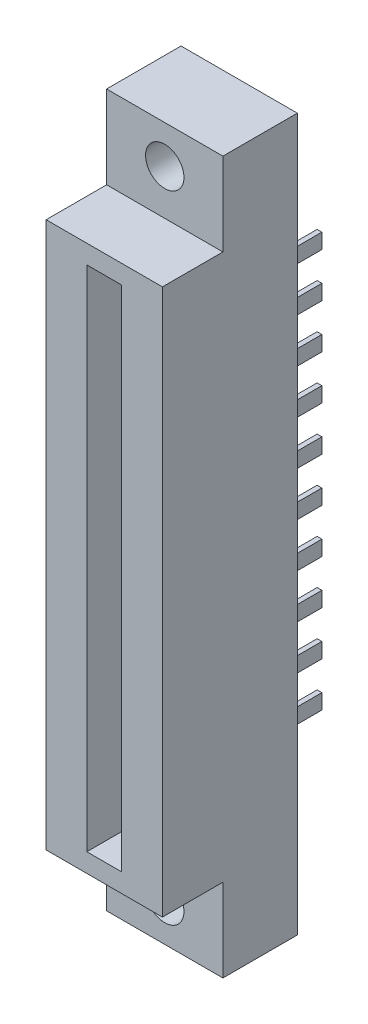
SolidWorks part; units mm, degrees
ref_plane "前视基准面" through (0, 0, 0) normal (0, 0, 1) x (1, 0, 0)
ref_plane "上视基准面" through (0, 0, 0) normal (0, 1, 0) x (1, 0, 0)
ref_plane "右视基准面" through (0, 0, 0) normal (1, 0, 0) x (0, 0, -1)
sketch "草图1" plane through (0, 0, 0) normal (0, 0, 1) x (1, 0, 0)
  line L0 (-109.3839, 0) -> (104.0581, 0) construction
  line L1 (0, 55.921) -> (0, -57.9694) construction
  line L3 (-5, 30.6) -> (5, 30.6)
  line L4 (-5, 30.6) -> (-5, -30.6)
  line L5 (-5, -30.6) -> (5, -30.6)
  line L6 (5, 30.6) -> (5, -30.6)
  dimension "D1" = 61.2
  dimension "D2" = 10
extrude "拉伸1" add sketch "草图1" along normal blind 6.4
sketch "草图2" plane through (0, 0, 6.4) normal (0, 0, 1) x (1, 0, 0)
  line L0 (-8.8552, 0) -> (12.3972, 0) construction
  line L1 (0, 34.0186) -> (0, -32.3951) construction
  line L3 (-5, 30.6) -> (-5, -30.6) construction
  line L4 (-5, 23.465) -> (5, 23.465)
  line L5 (-5, 23.465) -> (-5, -23.465)
  line L6 (-5, -23.465) -> (5, -23.465)
  line L7 (5, 23.465) -> (5, -23.465)
  line L8 (5, -30.6) -> (5, 30.6) construction
  dimension "D1" = 46.93
extrude "拉伸2" add sketch "草图2" along normal blind 5.2
sketch "草图3" plane through (0, 0, 6.4) normal (0, 0, 1) x (1, 0, 0)
  line L0 (-13.2827, 0) -> (15.9393, 0) construction
  line L1 (0, 37.0608) -> (0, -37.8999) construction
  circle A0 centre (0, 27.335) radius 1.65
  circle A1 centre (0, -27.335) radius 1.65
  dimension "D1" = 3.3
  dimension "D2" = 54.67
extrude "切除-拉伸1" cut sketch "草图3" against normal blind 15.3
sketch "草图4" plane through (0, 0, 0) normal (0, 0, -1) x (-1, 0, 0)
  line L0 (-14.0207, 1.905) -> (16.6772, 1.905) construction
  line L1 (0, 36.8227) -> (0, -37.1179) construction
  line L2 (-1.905, 0.2963) -> (-1.905, 4.0459) construction
  line L3 (-2.11, 2.555) -> (-1.7, 2.555)
  line L4 (-2.11, 2.555) -> (-2.11, 1.255)
  line L5 (-2.11, 1.255) -> (-1.7, 1.255)
  line L6 (-1.7, 2.555) -> (-1.7, 1.255)
  line L7 (1.905, 0.2963) -> (1.905, 4.0459) construction
  line L8 (1.7, 2.555) -> (1.7, 1.255)
  line L9 (2.11, 1.255) -> (1.7, 1.255)
  line L10 (2.11, 2.555) -> (2.11, 1.255)
  line L11 (2.11, 2.555) -> (1.7, 2.555)
  line L12 (-2.11, 6.365) -> (-1.7, 6.365)
  line L13 (-2.11, 6.365) -> (-2.11, 5.065)
  line L14 (-2.11, 5.065) -> (-1.7, 5.065)
  line L15 (-1.7, 6.365) -> (-1.7, 5.065)
  line L16 (1.7, 6.365) -> (1.7, 5.065)
  line L17 (2.11, 5.065) -> (1.7, 5.065)
  line L18 (2.11, 6.365) -> (2.11, 5.065)
  line L19 (2.11, 6.365) -> (1.7, 6.365)
  line L20 (-1.905, 4.1063) -> (-1.905, 7.8559) construction
  line L21 (1.905, 4.1063) -> (1.905, 7.8559) construction
  line L22 (-2.11, 10.175) -> (-1.7, 10.175)
  line L23 (-2.11, 10.175) -> (-2.11, 8.875)
  line L24 (-2.11, 8.875) -> (-1.7, 8.875)
  line L25 (-1.7, 10.175) -> (-1.7, 8.875)
  line L26 (1.7, 10.175) -> (1.7, 8.875)
  line L27 (2.11, 8.875) -> (1.7, 8.875)
  line L28 (2.11, 10.175) -> (2.11, 8.875)
  line L29 (2.11, 10.175) -> (1.7, 10.175)
  line L30 (-1.905, 7.9163) -> (-1.905, 11.6659) construction
  line L31 (1.905, 7.9163) -> (1.905, 11.6659) construction
  line L32 (-2.11, 13.985) -> (-1.7, 13.985)
  line L33 (-2.11, 13.985) -> (-2.11, 12.685)
  line L34 (-2.11, 12.685) -> (-1.7, 12.685)
  line L35 (-1.7, 13.985) -> (-1.7, 12.685)
  line L36 (1.7, 13.985) -> (1.7, 12.685)
  line L37 (2.11, 12.685) -> (1.7, 12.685)
  line L38 (2.11, 13.985) -> (2.11, 12.685)
  line L39 (2.11, 13.985) -> (1.7, 13.985)
  line L40 (-1.905, 11.7263) -> (-1.905, 15.4759) construction
  line L41 (1.905, 11.7263) -> (1.905, 15.4759) construction
  line L42 (-2.11, 17.795) -> (-1.7, 17.795)
  line L43 (-2.11, 17.795) -> (-2.11, 16.495)
  line L44 (-2.11, 16.495) -> (-1.7, 16.495)
  line L45 (-1.7, 17.795) -> (-1.7, 16.495)
  line L46 (1.7, 17.795) -> (1.7, 16.495)
  line L47 (2.11, 16.495) -> (1.7, 16.495)
  line L48 (2.11, 17.795) -> (2.11, 16.495)
  line L49 (2.11, 17.795) -> (1.7, 17.795)
  line L50 (-1.905, 15.5363) -> (-1.905, 19.2859) construction
  line L51 (1.905, 15.5363) -> (1.905, 19.2859) construction
  line L52 (-2.11, -1.255) -> (-1.7, -1.255)
  line L53 (-2.11, -1.255) -> (-2.11, -2.555)
  line L54 (-2.11, -2.555) -> (-1.7, -2.555)
  line L55 (-1.7, -1.255) -> (-1.7, -2.555)
  line L56 (1.7, -1.255) -> (1.7, -2.555)
  line L57 (2.11, -2.555) -> (1.7, -2.555)
  line L58 (2.11, -1.255) -> (2.11, -2.555)
  line L59 (2.11, -1.255) -> (1.7, -1.255)
  line L60 (-2.11, -5.065) -> (-1.7, -5.065)
  line L61 (-2.11, -5.065) -> (-2.11, -6.365)
  line L62 (-2.11, -6.365) -> (-1.7, -6.365)
  line L63 (-1.7, -5.065) -> (-1.7, -6.365)
  line L64 (1.7, -5.065) -> (1.7, -6.365)
  line L65 (2.11, -6.365) -> (1.7, -6.365)
  line L66 (2.11, -5.065) -> (2.11, -6.365)
  line L67 (2.11, -5.065) -> (1.7, -5.065)
  line L68 (-2.11, -8.875) -> (-1.7, -8.875)
  line L69 (-2.11, -8.875) -> (-2.11, -10.175)
  line L70 (-2.11, -10.175) -> (-1.7, -10.175)
  line L71 (-1.7, -8.875) -> (-1.7, -10.175)
  line L72 (1.7, -8.875) -> (1.7, -10.175)
  line L73 (2.11, -10.175) -> (1.7, -10.175)
  line L74 (2.11, -8.875) -> (2.11, -10.175)
  line L75 (2.11, -8.875) -> (1.7, -8.875)
  line L76 (-2.11, -12.685) -> (-1.7, -12.685)
  line L77 (-2.11, -12.685) -> (-2.11, -13.985)
  line L78 (-2.11, -13.985) -> (-1.7, -13.985)
  line L79 (-1.7, -12.685) -> (-1.7, -13.985)
  line L80 (1.7, -12.685) -> (1.7, -13.985)
  line L81 (2.11, -13.985) -> (1.7, -13.985)
  line L82 (2.11, -12.685) -> (2.11, -13.985)
  line L83 (2.11, -12.685) -> (1.7, -12.685)
  line L84 (-2.11, -16.495) -> (-1.7, -16.495)
  line L85 (-2.11, -16.495) -> (-2.11, -17.795)
  line L86 (-2.11, -17.795) -> (-1.7, -17.795)
  line L87 (-1.7, -16.495) -> (-1.7, -17.795)
  line L88 (1.7, -16.495) -> (1.7, -17.795)
  line L89 (2.11, -17.795) -> (1.7, -17.795)
  line L90 (2.11, -16.495) -> (2.11, -17.795)
  line L91 (2.11, -16.495) -> (1.7, -16.495)
  dimension "D1" = 1.905
  dimension "D2" = 1.3
  dimension "D3" = 0.41
  dimension "D4" = 3.81
  dimension "D5" = 5
  dimension "D6" = 6
extrude "拉伸3" add sketch "草图4" along normal blind 5
sketch "草图5" plane through (0, 0, 11.6) normal (0, 0, 1) x (1, 0, 0)
  line L0 (-15.4965, 0) -> (18.3007, 0) construction
  line L1 (0, 29.0007) -> (0, -23.465) construction
  line L2 (-5, -23.465) -> (5, -23.465) construction
  line L4 (-1.5, 21.85) -> (1.5, 21.85)
  line L5 (-1.5, 21.85) -> (-1.5, -21.85)
  line L6 (-1.5, -21.85) -> (1.5, -21.85)
  line L7 (1.5, 21.85) -> (1.5, -21.85)
  dimension "D1" = 3
  dimension "D2" = 43.7
extrude "切除-拉伸2" cut sketch "草图5" against normal blind 8
